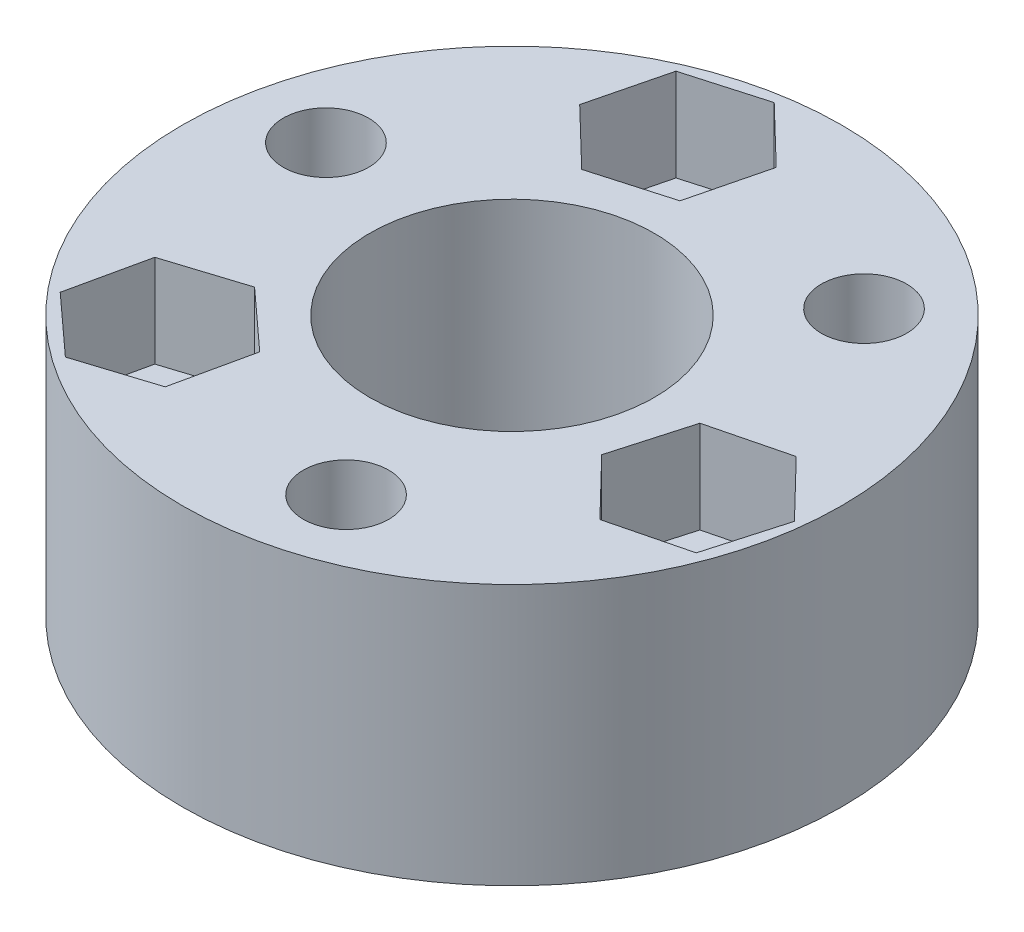
SolidWorks part; units mm, degrees
ref_plane "Plan de face" through (0, 0, 0) normal (0, 0, 1) x (1, 0, 0)
ref_plane "Plan de dessus" through (0, 0, 0) normal (0, 1, 0) x (1, 0, 0)
ref_plane "Plan de droite" through (0, 0, 0) normal (1, 0, 0) x (0, 0, -1)
sketch "Esquisse3" plane through (0, 0, 0) normal (0, 1, 0) x (1, 0, 0)
  circle A0 centre (0, 0) radius 13.9
  circle A1 centre (0, 0) radius 6
  circle A2 centre (0, 0) radius 10.5 construction
  circle A3 centre (-3.0505, 10.0471) radius 1.8
  circle A4 centre (7.1758, 7.6654) radius 1.8
  circle A5 centre (10.2263, -2.3817) radius 1.8
  circle A6 centre (3.0505, -10.0471) radius 1.8
  circle A7 centre (-7.1758, -7.6654) radius 1.8
  circle A8 centre (-10.2263, 2.3817) radius 1.8
  point P20 (0, 0)
  dimension "D1" = 27.8
  dimension "D2" = 12
  dimension "D3" = 21
  dimension "D4" = 3.6
extrude "Boss.-Extru.1" add sketch "Esquisse3" along normal blind 11
sketch "Esquisse4" plane through (0, 11, 0) normal (0, 1, 0) x (1, 0, 0)
  line L1 (-3.859, 6.7976) -> (-0.6406, 7.7221)
  line L2 (-0.6406, 7.7221) -> (0.168, 10.9717)
  line L3 (0.168, 10.9717) -> (-2.242, 13.2967)
  line L4 (-2.242, 13.2967) -> (-5.4604, 12.3721)
  line L5 (-5.4604, 12.3721) -> (-6.269, 9.1225)
  line L6 (-6.269, 9.1225) -> (-3.859, 6.7976)
  line L7 (12.5555, -4.7876) -> (13.4744, -1.5675)
  line L8 (13.4744, -1.5675) -> (11.1453, 0.8383)
  line L9 (11.1453, 0.8383) -> (7.8971, 0.0241)
  line L10 (7.8971, 0.0241) -> (6.9782, -3.1959)
  line L11 (6.9782, -3.1959) -> (9.3074, -5.6018)
  line L12 (9.3074, -5.6018) -> (12.5555, -4.7876)
  line L13 (-4.7013, -9.9215) -> (-3.9847, -6.6504)
  line L14 (-3.9847, -6.6504) -> (-6.4592, -4.3943)
  line L15 (-6.4592, -4.3943) -> (-9.6503, -5.4093)
  line L16 (-9.6503, -5.4093) -> (-10.3669, -8.6803)
  line L17 (-10.3669, -8.6803) -> (-7.8924, -10.9364)
  line L18 (-7.8924, -10.9364) -> (-4.7013, -9.9215)
  circle A0 centre (-3.0505, 10.0471) radius 2.9 construction
  circle A1 centre (10.2263, -2.3817) radius 2.9 construction
  circle A2 centre (-7.1758, -7.6654) radius 2.9 construction
  dimension "D1" = 5.8
extrude "Enlèv. mat.-Extru.1" cut sketch "Esquisse4" against normal blind 3.9
sketch "Esquisse5" plane through (0, 11, 0) normal (0, 1, 0) x (1, 0, 0)
  circle A0 centre (0, 0) radius 13.9 construction
  point P0 (-8.4589, -11.0299)
